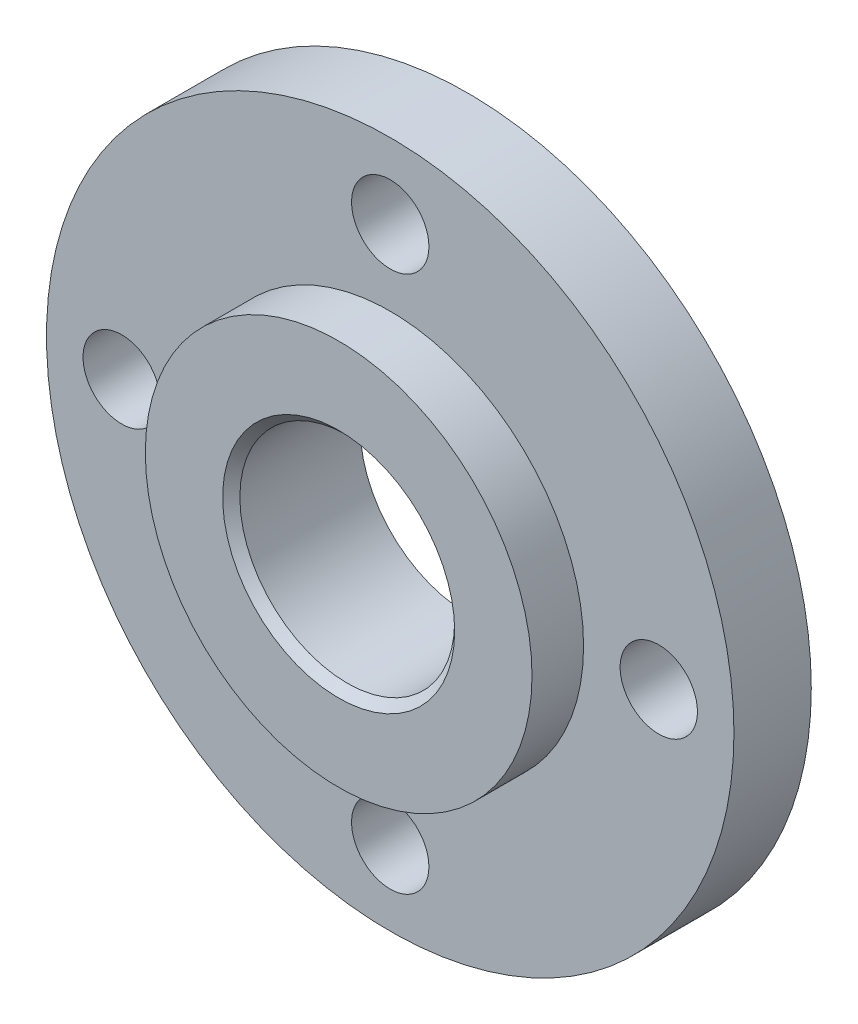
SolidWorks part; units mm, degrees
ref_plane "前视基准面" through (0, 0, 0) normal (0, 0, 1) x (1, 0, 0)
ref_plane "上视基准面" through (0, 0, 0) normal (0, 1, 0) x (1, 0, 0)
ref_plane "右视基准面" through (0, 0, 0) normal (1, 0, 0) x (0, 0, -1)
sketch "草图1" plane through (0, 0, 0) normal (0, 0, 1) x (1, 0, 0)
  circle A0 centre (0, 0) radius 80
extrude "凸台-拉伸1" add sketch "草图1" along normal blind 18
sketch "草图2" plane through (0, 0, 0) normal (0, 0, 1) x (1, 0, 0)
  circle A0 centre (0, 0) radius 45
extrude "凸台-拉伸2" add sketch "草图2" along normal blind 30
sketch "草图3" plane through (0, 0, 0) normal (0, 0, 1) x (1, 0, 0)
  circle A0 centre (0, 0) radius 25
extrude "切除-拉伸1" cut sketch "草图3" along normal through all
sketch "草图4" plane through (0, 0, 0) normal (0, 0, 1) x (1, 0, 0)
  line L0 (-78.125, 0) -> (78.125, 0) construction
  line L1 (0, -78.125) -> (0, 78.125) construction
  circle A0 centre (62.5, 0) radius 9
  circle A1 centre (0, 62.5) radius 9
  circle A2 centre (-62.5, 0) radius 9
  circle A3 centre (0, -62.5) radius 9
extrude "切除-拉伸2" cut sketch "草图4" along normal through all
chamfer "倒角1" distance 2 angle 45 1 edges at (25, 0, 30)
